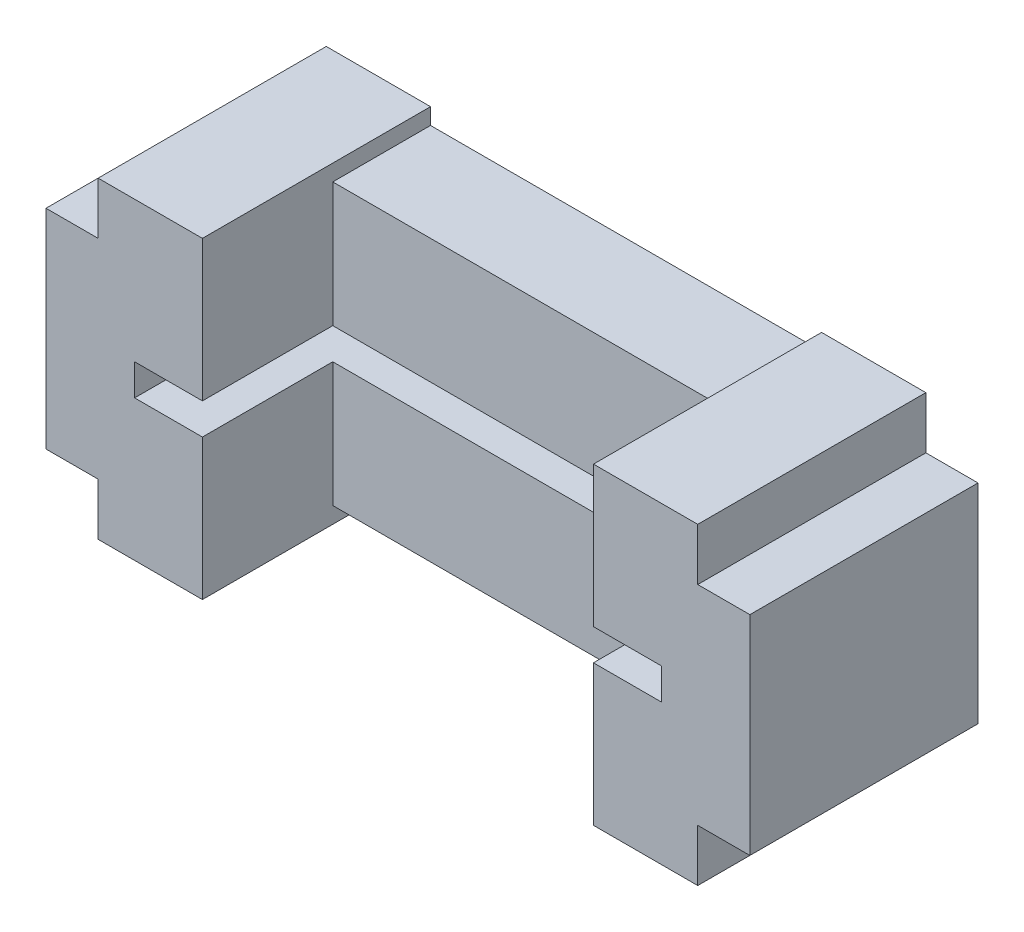
SolidWorks part; units mm, degrees
ref_plane "Front Plane" through (0, 0, 0) normal (0, 0, 1) x (1, 0, 0)
ref_plane "Top Plane" through (0, 0, 0) normal (0, 1, 0) x (1, 0, 0)
ref_plane "Right Plane" through (0, 0, 0) normal (1, 0, 0) x (0, 0, -1)
sketch "Sketch1" plane through (0, 0, 0) normal (0, 0, 1) x (1, 0, 0)
  line L1 (-29.21, -15.24) -> (29.21, -15.24)
  line L2 (-34.29, -10.16) -> (-34.29, 10.16)
  line L3 (-29.21, 15.24) -> (29.21, 15.24)
  line L4 (34.29, -10.16) -> (34.29, 10.16)
  line L9 (-34.29, 10.16) -> (-29.21, 10.16)
  line L10 (-29.21, 15.24) -> (-29.21, 10.16)
  line L13 (-34.29, -10.16) -> (-29.21, -10.16)
  line L14 (-29.21, -15.24) -> (-29.21, -10.16)
  line L17 (34.29, -10.16) -> (29.21, -10.16)
  line L18 (29.21, -15.24) -> (29.21, -10.16)
  line L21 (34.29, 10.16) -> (29.21, 10.16)
  line L22 (29.21, 15.24) -> (29.21, 10.16)
  point P0 (0, 0)
  point P2 (0, 15.24)
  point P4 (-34.29, 0)
  dimension "D1" = 68.58
  dimension "D2" = 30.48
  dimension "D3" = 5.08
extrude "Boss-Extrude1" add sketch "Sketch1" along normal blind 9.525
sketch "Sketch3" plane through (0, 0, 9.525) normal (0, 0, 1) x (1, 0, 0)
  line L0 (29.21, 15.24) -> (-29.21, 15.24) construction
  line L1 (-29.21, 15.24) -> (-19.05, 15.24)
  line L2 (-34.29, 10.16) -> (-34.29, -10.16)
  line L3 (-29.21, -15.24) -> (-19.05, -15.24)
  line L4 (-19.05, 15.24) -> (-19.05, 1.524)
  line L5 (-29.21, -15.24) -> (29.21, -15.24) construction
  line L6 (0, 0) -> (0, 15.24) construction
  line L7 (-19.05, 1.524) -> (-25.654, 1.524)
  line L9 (-19.05, -1.524) -> (-25.654, -1.524)
  line L10 (-25.654, 1.524) -> (-25.654, -1.524)
  line L11 (-19.05, -1.524) -> (-19.05, -15.24)
  line L12 (19.05, -1.524) -> (19.05, -15.24)
  line L13 (25.654, 1.524) -> (25.654, -1.524)
  line L14 (19.05, -1.524) -> (25.654, -1.524)
  line L15 (19.05, 1.524) -> (25.654, 1.524)
  line L16 (19.05, 15.24) -> (19.05, 1.524)
  line L17 (29.21, -15.24) -> (19.05, -15.24)
  line L18 (34.29, 10.16) -> (34.29, -10.16)
  line L19 (29.21, 15.24) -> (19.05, 15.24)
  line L20 (-34.29, 10.16) -> (-34.29, -10.16) construction
  line L21 (29.21, -15.24) -> (29.21, -10.16) construction
  line L24 (-34.29, 10.16) -> (-29.21, 10.16)
  line L25 (-29.21, 15.24) -> (-29.21, 10.16)
  line L26 (-29.21, -10.16) -> (-34.29, -10.16)
  line L27 (-29.21, -10.16) -> (-29.21, -15.24)
  line L32 (34.29, -10.16) -> (29.21, -10.16)
  line L33 (29.21, -15.24) -> (29.21, -10.16)
  line L34 (29.21, -10.16) -> (34.29, -10.16) construction
  line L37 (34.29, 10.16) -> (29.21, 10.16)
  line L38 (29.21, 15.24) -> (29.21, 10.16)
  line L39 (34.29, -10.16) -> (34.29, 10.16) construction
  point P12 (-25.654, 0)
  dimension "D1" = 6.604
  dimension "D2" = 3.048
  dimension "D4" = 19.05
extrude "Boss-Extrude2" add sketch "Sketch3" along normal blind 12.7
sketch "Sketch4" plane through (0, 0, 9.525) normal (0, 0, 1) x (1, 0, 0)
  line L1 (-25.654, -1.524) -> (25.654, -1.524)
  line L2 (-25.654, -1.524) -> (-25.654, 1.524)
  line L3 (-25.654, 1.524) -> (25.654, 1.524)
  line L4 (25.654, -1.524) -> (25.654, 1.524)
extrude "Cut-Extrude1" cut sketch "Sketch4" against normal blind 6.096
sketch "Sketch5" plane through (0, 0, 9.525) normal (0, 0, 1) x (1, 0, 0)
  line L0 (19.05, 15.24) -> (-19.05, 15.24) construction
  line L1 (-19.05, 15.24) -> (19.05, 15.24)
  line L2 (-19.05, 15.24) -> (-19.05, 13.6525)
  line L3 (-19.05, 13.6525) -> (19.05, 13.6525)
  line L4 (19.05, 15.24) -> (19.05, 13.6525)
  line L5 (0, 0) -> (12.7, 0) construction
  line L6 (19.05, -15.24) -> (19.05, -13.6525)
  line L7 (-19.05, -13.6525) -> (19.05, -13.6525)
  line L8 (-19.05, -15.24) -> (-19.05, -13.6525)
  line L9 (-19.05, -15.24) -> (19.05, -15.24)
  line L10 (-19.05, 1.524) -> (-19.05, 15.24) construction
  point P6 (0, 13.6525)
  dimension "D1" = 1.5875
extrude "Cut-Extrude2" cut sketch "Sketch5" against normal through all both and the other way through all
